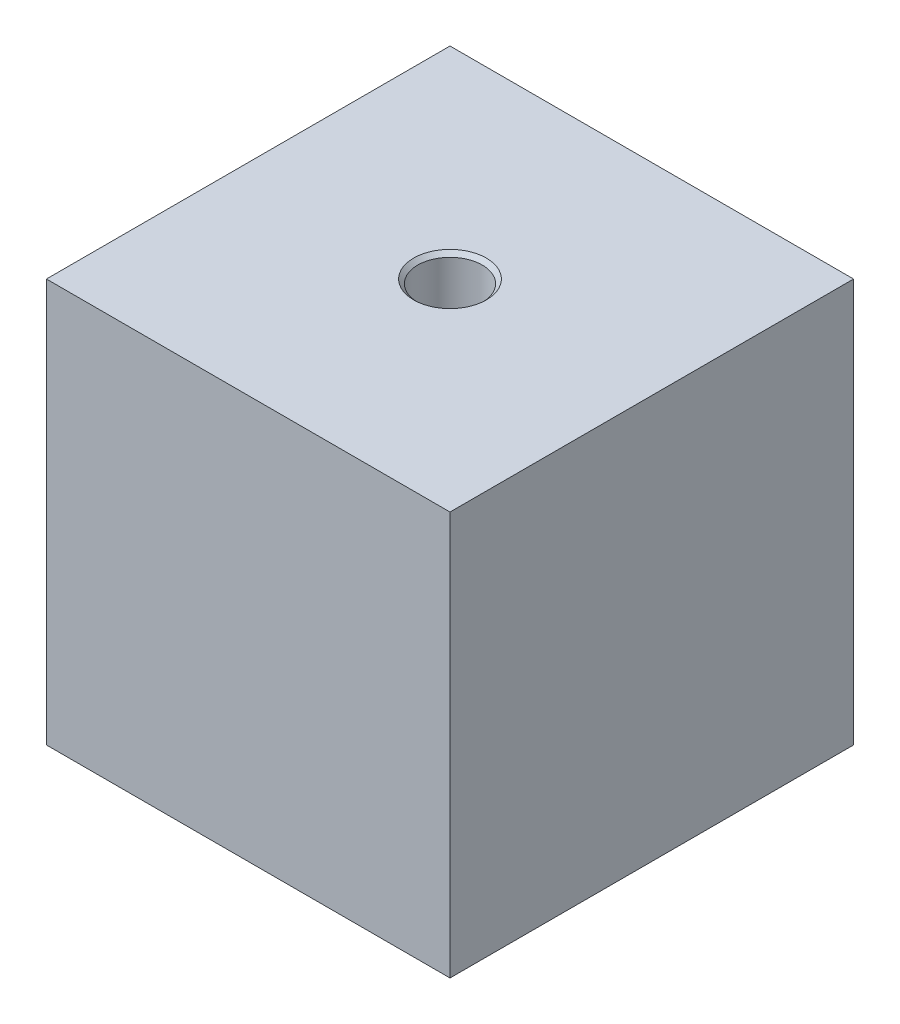
SolidWorks part; units mm, degrees
ref_plane "Přední rovina" through (0, 0, 0) normal (0, 0, 1) x (1, 0, 0)
ref_plane "Horní rovina" through (0, 0, 0) normal (0, 1, 0) x (1, 0, 0)
ref_plane "Pravá rovina" through (0, 0, 0) normal (1, 0, 0) x (0, 0, -1)
sketch "Skica1" plane through (0, 0, 0) normal (0, 0, 1) x (1, 0, 0)
  line L1 (-25, -25) -> (25, -25)
  line L2 (-25, -25) -> (-25, 25)
  line L3 (-25, 25) -> (25, 25)
  line L4 (25, -25) -> (25, 25)
  line L5 (-25, -25) -> (25, 25) construction
  line L6 (-25, 25) -> (25, -25) construction
  point P0 (0, 0)
  dimension "D1" = 50
  dimension "D2" = 50
extrude "Přidat vysunutím1" add sketch "Skica1" along normal blind 50
sketch "Skica2" plane through (0, 25, 0) normal (0, 1, 0) x (1, 0, 0)
  line L0 (-25, -25) -> (25, -25) construction
  line L1 (-25, -50) -> (-25, 0) construction
  line L2 (25, -50) -> (25, 0) construction
  circle A0 centre (0, -25) radius 2.05
  dimension "D1" = 4.1
extrude "Odebrat vysunutím1" cut sketch "Skica2" against normal up to surface (50 mm away) up to face at (0, -25, 25)
sketch "Skica3" plane through (0, 25, 0) normal (0, 1, 0) x (1, 0, 0)
  circle A0 centre (0, -25) radius 4
  dimension "D1" = 8
extrude "Odebrat vysunutím2" cut sketch "Skica3" against normal blind 25
chamfer "Zkosení1" distance 0.5 angle 45 1 edges at (0, 25, 29)
chamfer "Zkosení2" distance 0.5 angle 45 1 edges at (0, 0, 27.05)
